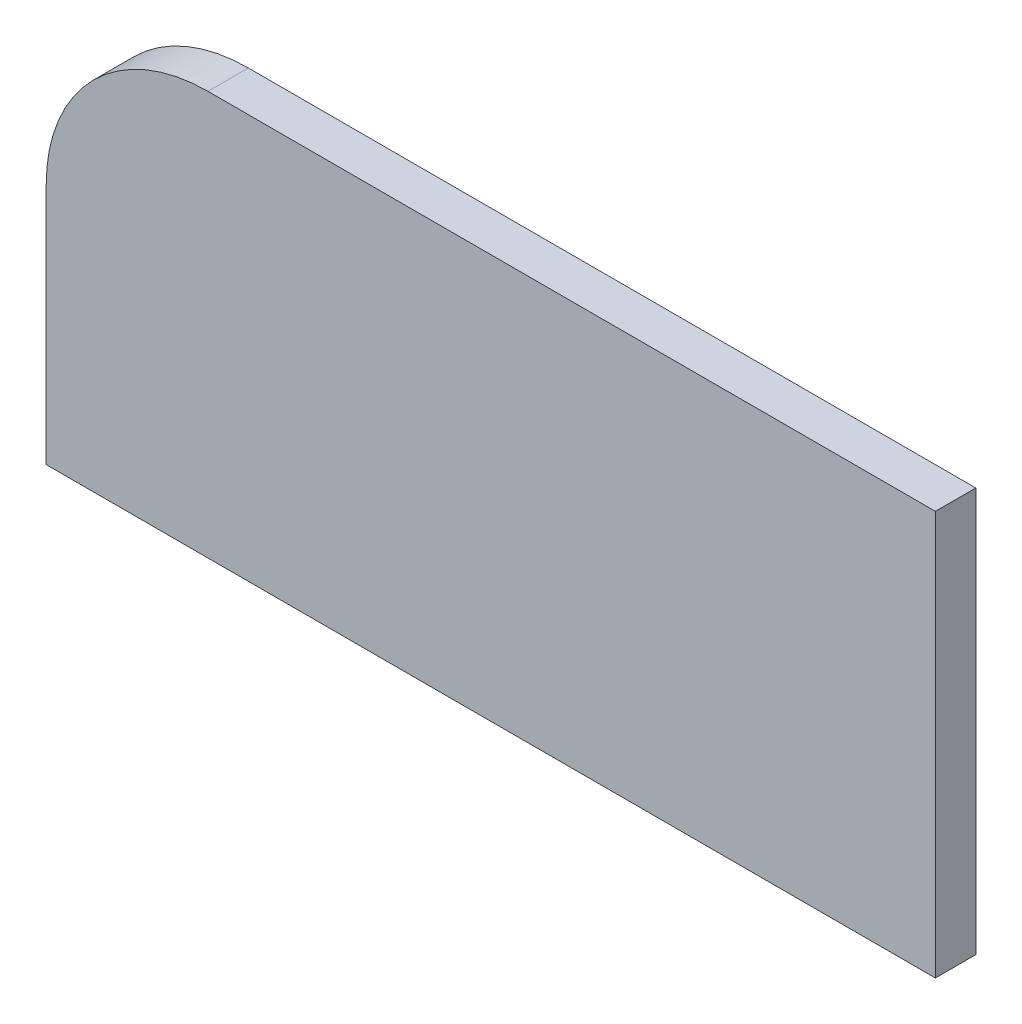
SolidWorks part; units mm, degrees
ref_plane "Front Plane" through (0, 0, 0) normal (0, 0, 1) x (1, 0, 0)
ref_plane "Top Plane" through (0, 0, 0) normal (0, 1, 0) x (1, 0, 0)
ref_plane "Right Plane" through (0, 0, 0) normal (1, 0, 0) x (0, 0, -1)
sketch "Sketch1" plane through (0, 0, 0) normal (0, 0, 1) x (1, 0, 0)
  line L1 (0, 0) -> (110, 0)
  line L2 (0, 0) -> (0, 50)
  line L3 (0, 50) -> (110, 50)
  line L4 (110, 0) -> (110, 50)
  dimension "D1" = 110
  dimension "D2" = 50
extrude "Boss-Extrude1" add sketch "Sketch1" along normal blind 5
fillet "Fillet1" radius 20 1 edges at (0, 50, 2.5)
